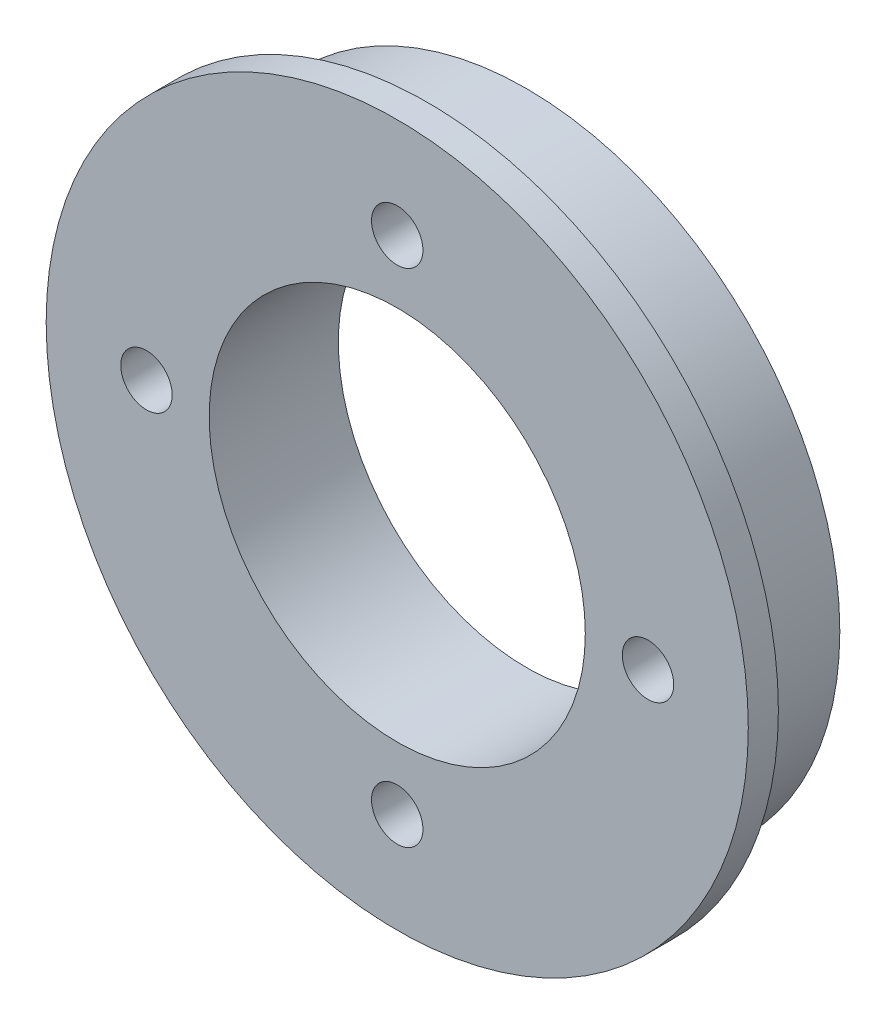
SolidWorks part; units mm, degrees
material "6061 合金"
ref_plane "前视基准面" through (0, 0, 0) normal (0, 0, 1) x (1, 0, 0)
ref_plane "上视基准面" through (0, 0, 0) normal (0, 1, 0) x (1, 0, 0)
ref_plane "右视基准面" through (0, 0, 0) normal (1, 0, 0) x (0, 0, -1)
sketch "草图1" plane through (0, 0, 0) normal (0, 0, 1) x (1, 0, 0)
  circle A0 centre (0, 0) radius 12.5
  circle A1 centre (0, 0) radius 7.5
  dimension "D1" = 25
  dimension "D2" = 5
extrude "凸台-拉伸1" add sketch "草图1" along normal blind 3.95
sketch "草图2" plane through (0, 0, 3.95) normal (0, 0, 1) x (1, 0, 0)
  circle A0 centre (0, 0) radius 14
  circle A1 centre (0, 0) radius 12.5 construction
  circle A2 centre (0, 0) radius 7.5 construction
  circle A3 centre (0, 0) radius 7.5
  dimension "D1" = 1.5
extrude "凸台-拉伸2" add sketch "草图2" along normal blind 1.2
sketch "草图3" plane through (0, 0, 0) normal (0, 0, -1) x (-1, 0, 0)
  circle A0 centre (0, 0) radius 10 construction
  circle A1 centre (0, 0) radius 12.5 construction
  dimension "D1" = 2.5
hole_wizard "M2.5 螺纹孔1" positions "草图4" profile "草图5" tap size "M2.5" standard "GB" end condition through all
sketch "草图4" plane through (0, 0, 0) normal (0, 0, -1) x (-1, 0, 0)
  line L0 (0, 10) -> (0, 0) construction
  circle A0 centre (0, 0) radius 10 construction
  point P0 (0, 10)
sketch "草图5" plane through (0, 10, 0) normal (1, 0, 0) x (0, 1, 0)
  line L0 (0, 0) -> (0, 5.15)
  line L1 (0, 5.15) -> (1.025, 5.15)
  line L2 (1.025, 5.15) -> (1.025, 0)
  line L5 (1.025, 0) -> (0, 0)
  line L11 (0, -6.35) -> (0, 107.95) construction
  dimension "通孔螺纹孔钻头直径" = 2.05
  dimension "通孔螺纹孔钻头深度" = 5.15
cosmetic thread "孔螺蚊线1"
pattern_circular "阵列(圆周)1" count 4 over 360 about axis through (0, 0, 0) along (0, 0, 1) of "M2.5 螺纹孔1"
cosmetic thread "孔螺蚊线2"
cosmetic thread "孔螺蚊线3"
cosmetic thread "孔螺蚊线4"
